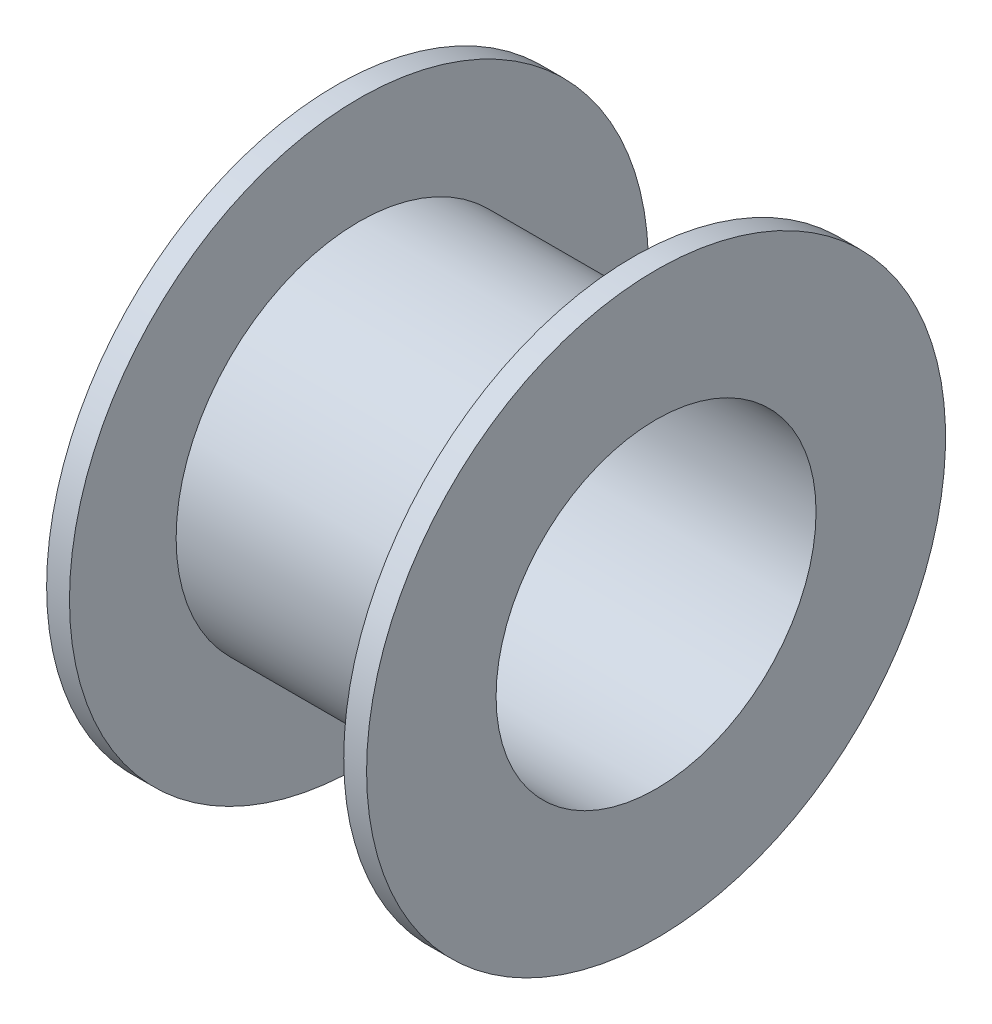
SolidWorks part; units mm, degrees
ref_plane "Спереди" through (0, 0, 0) normal (0, 0, 1) x (1, 0, 0)
ref_plane "Сверху" through (0, 0, 0) normal (0, 1, 0) x (1, 0, 0)
ref_plane "Справа" through (0, 0, 0) normal (1, 0, 0) x (0, 0, -1)
sketch "Эскиз1" plane through (0, 0, 0) normal (0, 0, 1) x (1, 0, 0)
  line L0 (-23.8371, 0) -> (46.374, 0) construction
  line L1 (19.5, 19) -> (21, 19)
  line L3 (0, 10.5) -> (0, 19)
  line L4 (0, 19) -> (1.5, 19)
  line L5 (21, 10.5) -> (21, 19)
  line L6 (1.5, 19) -> (1.5, 12)
  line L7 (1.5, 12) -> (19.5, 12)
  line L8 (19.5, 19) -> (19.5, 12)
  line L9 (0, 10.5) -> (21, 10.5)
  dimension "D1" = 21
  dimension "D2" = 21
  dimension "D3" = 1.5
  dimension "D4" = 1.5
  dimension "D5" = 24
  dimension "D6" = 19
revolve "Повернуть1" add sketch "Эскиз1" angle 360 about L0
